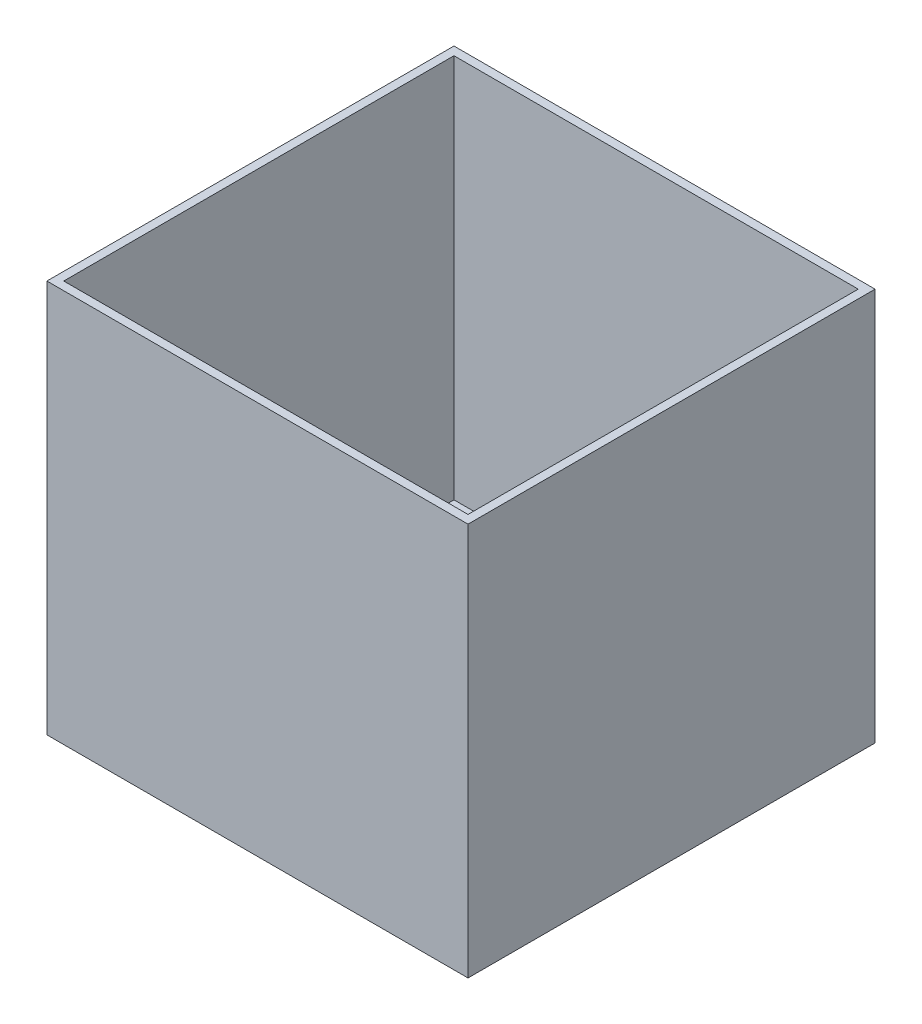
SolidWorks part; units mm, degrees
ref_plane "Front Plane" through (0, 0, 0) normal (0, 0, 1) x (1, 0, 0)
ref_plane "Top Plane" through (0, 0, 0) normal (0, 1, 0) x (1, 0, 0)
ref_plane "Right Plane" through (0, 0, 0) normal (1, 0, 0) x (0, 0, -1)
sketch "Sketch2" plane through (0, 0, 0) normal (0, 1, 0) x (1, 0, 0)
  line L1 (-75, 72.5) -> (75, 72.5)
  line L2 (-75, 72.5) -> (-75, -72.5)
  line L3 (-75, -72.5) -> (75, -72.5)
  line L4 (75, 72.5) -> (75, -72.5)
  line L5 (0, -72.5) -> (0, 72.5) construction
  line L6 (-75, 0) -> (75, 0) construction
  point P0 (0, 0)
  dimension "D1" = 145
  dimension "D2" = 150
extrude "Boss-Extrude2" add sketch "Sketch2" along normal blind 140
shell "Shell1" thickness 3
sketch "Sketch4" plane through (0, 140, 0) normal (0, 1, 0) x (1, 0, 0)
  line L0 (-72, 69.5) -> (-72, -69.5)
  line L1 (-72, -69.5) -> (72, -69.5)
  line L2 (72, -69.5) -> (72, 69.5)
  line L3 (72, 69.5) -> (-72, 69.5)
  line L4 (75, -72.5) -> (75, 72.5)
  line L5 (75, 72.5) -> (-75, 72.5)
  line L6 (-75, 72.5) -> (-75, -72.5)
  line L7 (-75, -72.5) -> (75, -72.5)
  line L8 (75, -72.5) -> (75, 72.5)
  line L9 (75, 72.5) -> (-75, 72.5)
  line L10 (-75, 72.5) -> (-75, -72.5)
  line L11 (-75, -72.5) -> (75, -72.5)
  dimension "D1" = 0
  dimension "D2" = 3
extrude "Cut-Extrude3" cut sketch "Sketch4" against normal blind 5 contours L2 L3 L0 L1
